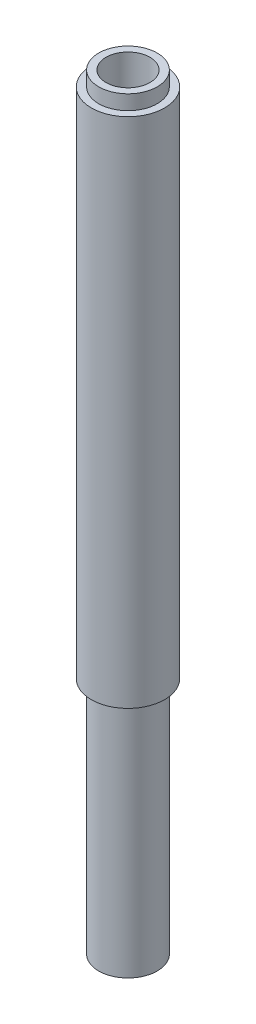
SolidWorks part; units mm, degrees
ref_plane "Front Plane" through (0, 0, 0) normal (0, 0, 1) x (1, 0, 0)
ref_plane "Top Plane" through (0, 0, 0) normal (0, 1, 0) x (1, 0, 0)
ref_plane "Right Plane" through (0, 0, 0) normal (1, 0, 0) x (0, 0, -1)
sketch "Sketch1" plane through (0, 0, 0) normal (0, 1, 0) x (1, 0, 0)
  circle A0 centre (0, 0) radius 12.7
  dimension "D1" = 25.4
extrude "Boss-Extrude1" add sketch "Sketch1" along normal blind 177.8
sketch "Sketch4" plane through (0, 177.8, 0) normal (0, 1, 0) x (1, 0, 0)
  circle A2 centre (0, 0) radius 10.16
  circle A3 centre (0, 0) radius 10.16
  dimension "D1" = 2.54
extrude "Boss-Extrude2" add sketch "Sketch4" along normal blind 5.08
sketch "Sketch5" plane through (0, 182.88, 0) normal (0, 1, 0) x (1, 0, 0)
  circle A0 centre (0, 0) radius 10.16 construction
  circle A1 centre (0, 0) radius 10.16 construction
  circle A2 centre (0, 0) radius 7.62
  dimension "D1" = 2.54
extrude "Cut-Extrude1" cut sketch "Sketch5" against normal through all
sketch "Sketch6" plane through (0, 0, 0) normal (0, -1, 0) x (1, 0, 0)
  circle A0 centre (0, 0) radius 10.16
  circle A1 centre (0, 0) radius 7.62 construction
  circle A2 centre (0, 0) radius 7.62
  dimension "D1" = 20.32
extrude "Boss-Extrude3" add sketch "Sketch6" along normal blind 82.804
sketch "Sketch7" plane through (0, -82.804, 0) normal (0, -1, 0) x (1, 0, 0)
  circle A0 centre (0, 0) radius 12.7 construction
  circle A1 centre (0, 0) radius 12.7
